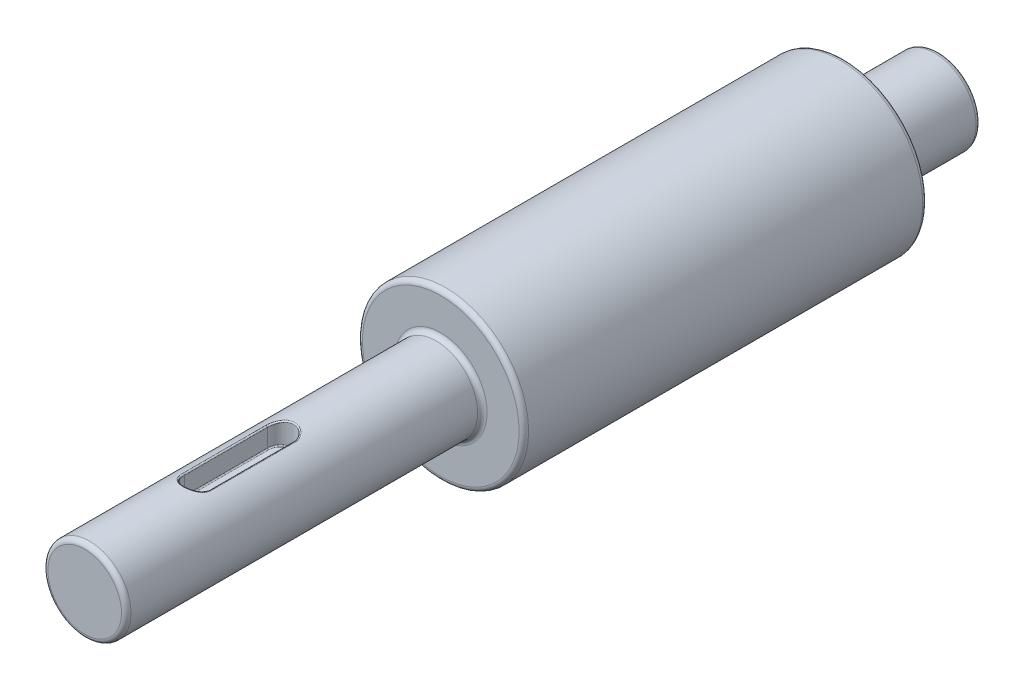
SolidWorks part; units mm, degrees
material "Stainless Steel (ferritic)"
ref_plane "Front Plane" through (0, 0, 0) normal (0, 0, 1) x (1, 0, 0)
ref_plane "Top Plane" through (0, 0, 0) normal (0, 1, 0) x (1, 0, 0)
ref_plane "Right Plane" through (0, 0, 0) normal (1, 0, 0) x (0, 0, -1)
sketch "Sketch1" plane through (0, 0, 0) normal (0, 0, 1) x (1, 0, 0)
  circle A0 centre (0, 0) radius 35
  dimension "D1" = 70
extrude "Boss-Extrude1" add sketch "Sketch1" along normal mid plane 170
sketch "Sketch2" plane through (0, 0, 85) normal (0, 0, 1) x (1, 0, 0)
  circle A0 centre (0, 0) radius 17.5
  dimension "D1" = 35
extrude "Boss-Extrude2" add sketch "Sketch2" along normal blind 150
sketch "Sketch3" plane through (0, 0, -85) normal (0, 0, -1) x (-1, 0, 0)
  circle A0 centre (0, 0) radius 17.5
  dimension "D1" = 35
extrude "Boss-Extrude3" add sketch "Sketch3" along normal blind 40
fillet "Fillet1" radius 2 5 edges at (17.5, 0, 235) (-17.5, 0, -125) (35, 0, -85) (17.5, 0, 85) (35, 0, 85)
ref_plane "Plane1" through (0, 8, 0) normal (0, 1, 0) x (1, 0, 0)
sketch "Sketch4" plane through (0, 8, 0) normal (0, 1, 0) x (1, 0, 0)
  line L0 (0, -187.5) -> (0, -152.5) construction
  line L1 (-5.5, -187.5) -> (-5.5, -152.5)
  line L2 (5.5, -187.5) -> (5.5, -152.5)
  arc A0 (-5.5, -187.5) -> (5.5, -187.5) centre (0, -187.5) ccw
  arc A1 (5.5, -152.5) -> (-5.5, -152.5) centre (0, -152.5) ccw
  point P3 (0, -170)
  dimension "D1" = 170
  dimension "D2" = 35
  dimension "D3" = 11
extrude "Cut-Extrude1" cut sketch "Sketch4" along normal up to next
fillet "Fillet2" radius 0.5 8 edges at (-0.5093, 17.4926, 192.9764) (5.5, 16.6132, 170) (0.5093, 17.4926, 147.0236) (0, 8, 147) (5.5, 8, 170) (0, 8, 193) (-5.5, 16.6132, 170) (-5.5, 8, 170)
